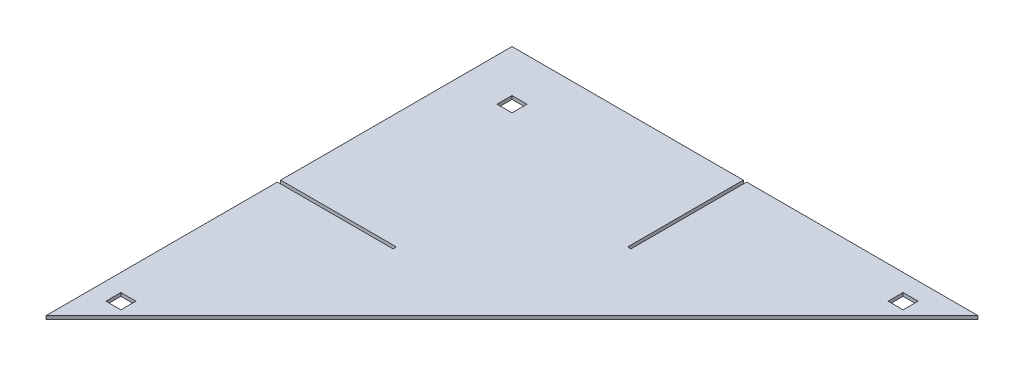
SolidWorks part; units mm, degrees
material "Beech"
ref_plane "Front Plane" through (0, 0, 0) normal (0, 0, 1) x (1, 0, 0)
ref_plane "Top Plane" through (0, 0, 0) normal (0, 1, 0) x (1, 0, 0)
ref_plane "Right Plane" through (0, 0, 0) normal (1, 0, 0) x (0, 0, -1)
sketch "Sketch1" plane through (0, 0, 0) normal (0, 1, 0) x (1, 0, 0)
  line L0 (52.0383, -43.6128) -> (52.0383, -16.2731) construction
  line L1 (122.0383, 26.301) -> (52.5383, 26.301)
  line L2 (51.5383, -8.449) -> (52.5383, -8.449)
  line L3 (51.5383, -8.449) -> (51.5383, 26.301)
  line L4 (-17.9617, 26.301) -> (-17.9617, -43.199)
  line L5 (122.0383, 26.301) -> (-17.9617, -113.699)
  line L6 (-19.215, 11.301) -> (3.6084, 11.301) construction
  line L7 (52.5383, -8.449) -> (52.5383, 26.301)
  line L8 (51.5383, -8.449) -> (52.5383, 26.301) construction
  line L9 (51.5383, 26.301) -> (52.5383, -8.449) construction
  line L10 (38.6915, -43.699) -> (16.328, -43.699) construction
  line L11 (-17.9617, -44.199) -> (-17.9617, -113.699)
  line L12 (16.7883, -44.199) -> (-17.9617, -44.199)
  line L13 (16.7883, -44.199) -> (16.7883, -43.199)
  line L14 (16.7883, -43.199) -> (-17.9617, -43.199)
  line L15 (51.5383, 26.301) -> (-17.9617, 26.301)
  line L16 (16.7883, -44.199) -> (-17.9617, -43.199) construction
  line L17 (16.7883, -43.199) -> (-17.9617, -44.199) construction
  line L18 (-5.2117, 13.551) -> (-0.7117, 13.551)
  line L19 (-5.2117, 13.551) -> (-5.2117, 9.051)
  line L20 (-5.2117, 9.051) -> (-0.7117, 9.051)
  line L21 (-0.7117, 13.551) -> (-0.7117, 9.051)
  line L22 (-5.2117, 13.551) -> (-0.7117, 9.051) construction
  line L23 (-5.2117, 9.051) -> (-0.7117, 13.551) construction
  line L24 (104.7883, 21.051) -> (109.2883, 21.051)
  line L25 (104.7883, 21.051) -> (104.7883, 16.551)
  line L26 (104.7883, 16.551) -> (109.2883, 16.551)
  line L27 (109.2883, 21.051) -> (109.2883, 16.551)
  line L28 (104.7883, 21.051) -> (109.2883, 16.551) construction
  line L29 (104.7883, 16.551) -> (109.2883, 21.051) construction
  line L30 (107.0383, 11.301) -> (107.0383, 26.301) construction
  line L31 (52.0383, -43.699) -> (-20.4617, 28.801) construction
  line L32 (-8.2117, -96.449) -> (-12.7117, -100.949) construction
  line L33 (-12.7117, -96.449) -> (-8.2117, -100.949) construction
  line L34 (-12.7117, -100.949) -> (-8.2117, -100.949)
  line L35 (-8.2117, -96.449) -> (-8.2117, -100.949)
  line L36 (-12.7117, -96.449) -> (-8.2117, -96.449)
  line L37 (-12.7117, -96.449) -> (-12.7117, -100.949)
  point P0 (52.0383, -43.699)
  point P3 (52.0383, 8.926)
  point P9 (107.0383, 18.801)
  point P13 (-0.5867, -43.699)
  point P20 (-2.9617, 11.301)
  point P32 (107.0383, 18.801)
  point P39 (-10.4617, -98.699)
  dimension "D2" = 4.5
  dimension "D1" = 140
  dimension "D3" = 1
  dimension "D7" = 34.75
  dimension "D4" = 15
  dimension "D5" = 15
  dimension "D6" = 15
extrude "Boss-Extrude3" add sketch "Sketch1" along normal blind 1
equation "\"SideLength\"=140"
equation "\"D1@Sketch1\" = \"SideLength\""
equation "\"D7@Sketch1\"=\"SideLength\"/4-\"MaterialThickness2\"/4"
equation "\"dead\"= 1"
equation "\"ZapstrapThickness\"=0.45"
equation "\"MaterialThickness2\"= 1"
equation "\"D1@Boss-Extrude3\"=\"MaterialThickness2\""
